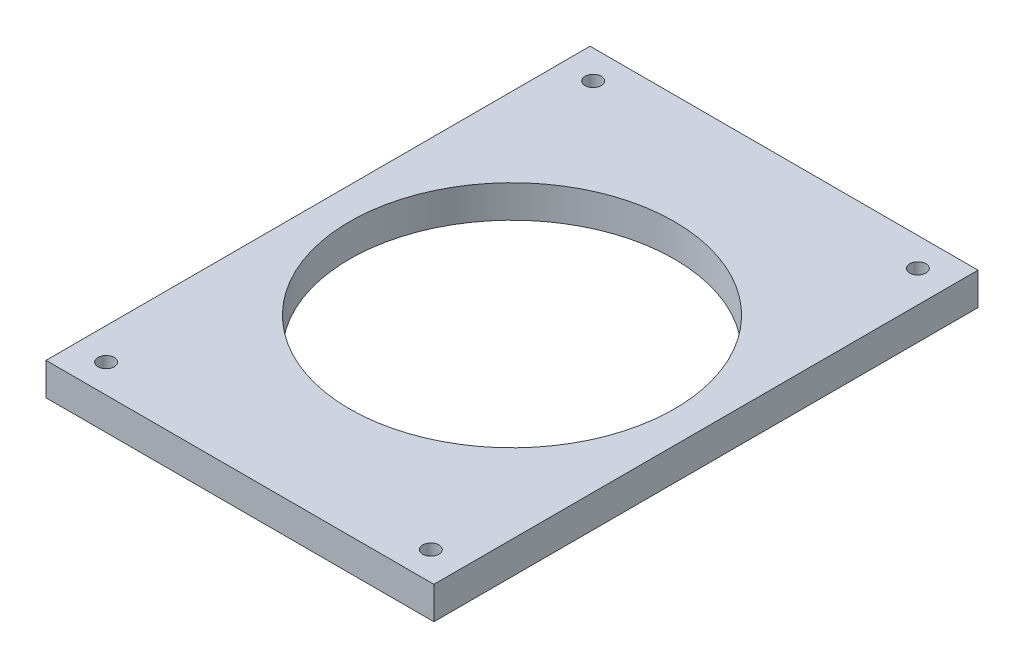
SolidWorks part; units mm, degrees
ref_plane "Front Plane" through (0, 0, 0) normal (0, 0, 1) x (1, 0, 0)
ref_plane "Top Plane" through (0, 0, 0) normal (0, 1, 0) x (1, 0, 0)
ref_plane "Right Plane" through (0, 0, 0) normal (1, 0, 0) x (0, 0, -1)
sketch "Sketch1" plane through (0, 0, 0) normal (0, 1, 0) x (1, 0, 0)
  line L1 (-50, 75) -> (50, 75) construction
  line L2 (-50, 75) -> (-50, -75) construction
  line L3 (-50, -75) -> (50, -75) construction
  line L4 (50, 75) -> (50, -75) construction
  line L5 (-50, 75) -> (50, -75) construction
  line L6 (-50, -75) -> (50, 75) construction
  line L7 (-59.7349, 83.7865) -> (59.7349, 83.7865)
  line L8 (-59.7349, 83.7865) -> (-59.7349, -83.7865)
  line L9 (-59.7349, -83.7865) -> (59.7349, -83.7865)
  line L10 (59.7349, 83.7865) -> (59.7349, -83.7865)
  line L11 (-59.7349, 83.7865) -> (59.7349, -83.7865) construction
  line L12 (-59.7349, -83.7865) -> (59.7349, 83.7865) construction
  circle A0 centre (0, 0) radius 50
  circle A1 centre (50, 75) radius 2.5
  circle A2 centre (-50, 75) radius 2.5
  circle A3 centre (-50, -75) radius 2.5
  circle A4 centre (50, -75) radius 2.5
  dimension "D1" = 100
  dimension "D4" = 5
  dimension "D5" = 5
  dimension "D6" = 5
  dimension "D7" = 5
  dimension "D2" = 150
  dimension "D3" = 100
extrude "Boss-Extrude1" add sketch "Sketch1" along normal blind 10
